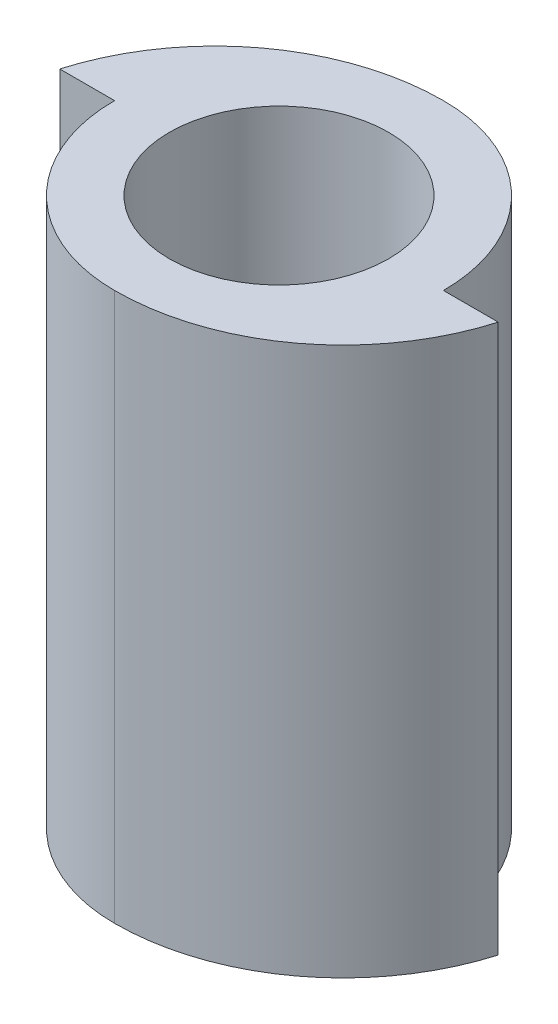
SolidWorks part; units mm, degrees
ref_plane "정면" through (0, 0, 0) normal (0, 0, 1) x (1, 0, 0)
ref_plane "윗면" through (0, 0, 0) normal (0, 1, 0) x (1, 0, 0)
ref_plane "우측면" through (0, 0, 0) normal (1, 0, 0) x (0, 0, -1)
sketch "스케치1" plane through (0, 0, 0) normal (0, 0, 1) x (1, 0, 0)
  line L0 (20, -7) -> (20, -10) construction
  line L1 (0, 0) -> (40, 0)
  line L2 (0, 0) -> (0, -40)
  line L3 (0, -40) -> (40, -40)
  line L4 (40, 0) -> (40, -40)
  line L5 (17, -10) -> (23, -10)
  line L6 (17, -10) -> (17, -31)
  line L7 (17, -31) -> (23, -31)
  line L8 (23, -10) -> (23, -31)
  line L9 (19, -10) -> (21, -10)
  line L10 (19, -10) -> (19, -7)
  line L11 (19, -7) -> (21, -7)
  line L12 (21, -10) -> (21, -7)
  line L13 (20, -10) -> (20, -40) construction
  line L14 (5, 5) -> (35, 5) construction
  line L15 (5, 5) -> (5, -10)
  line L16 (5, -10) -> (10, -10)
  line L17 (10, -10) -> (10, 5)
  line L18 (30, 5) -> (30, -35)
  line L19 (30, -35) -> (35, -35)
  line L20 (35, -35) -> (35, 5)
  line L22 (4, -4) -> (30, -4)
  line L23 (4, -4) -> (4, -8)
  line L24 (4, -8) -> (30, -8)
  line L25 (30, -4) -> (30, -8)
  line L26 (18, -4) -> (22, -4)
  line L27 (18, -4) -> (18, -9)
  line L28 (18, -9) -> (22, -9)
  line L29 (22, -4) -> (22, -9)
  arc A0 (10, 5) -> (30, 5) centre (20, 5) cw
  arc A1 (5, 5) -> (35, 5) centre (20, 5) cw
  point P30 (20, -9)
  dimension "D7" = 5
  dimension "D8" = 10
  dimension "D1" = 2
  dimension "D2" = 3
  dimension "D3" = 21
  dimension "D4" = 6
  dimension "D5" = 40
  dimension "D6" = 40
  dimension "D9" = 40
  dimension "D10" = 15
  dimension "D11" = 10
  dimension "D12" = 5
  dimension "D13" = 4
  dimension "D14" = 4
  dimension "D15" = 5
  dimension "D16" = 2
  dimension "D17" = 1
sketch "스케치2" plane through (0, 0, 0) normal (0, 1, 0) x (1, 0, 0)
  line L1 (0, 0) -> (40, 0) construction
  line L2 (-2, 0) -> (2, 0)
  circle A0 centre (0, 0) radius 1.5
  arc A1 (0, -1.5) -> (2, 0) centre (0, 0.5833) ccw
  arc A2 (0, 1.5) -> (-2, 0) centre (0, -0.5833) ccw
  circle A3 centre (0, 0) radius 1
  dimension "D1" = 3
  dimension "D3" = 2
  dimension "D2" = 4
extrude "보스-돌출1" add sketch "스케치2" along normal blind 5 contours A3 L2 A0 | A3 L2 A0 | A0 A1 L2 | A0 A2 L2
